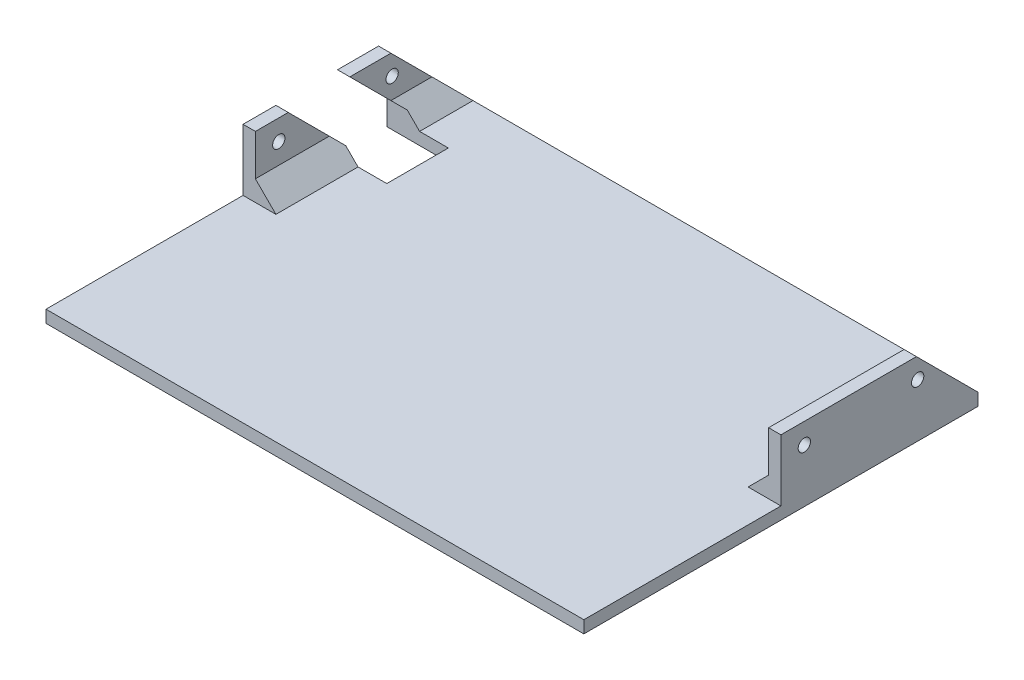
SolidWorks part; units mm, degrees
ref_plane "Front Plane" through (0, 0, 0) normal (0, 0, 1) x (1, 0, 0)
ref_plane "Top Plane" through (0, 0, 0) normal (0, 1, 0) x (1, 0, 0)
ref_plane "Right Plane" through (0, 0, 0) normal (1, 0, 0) x (0, 0, -1)
sketch "Sketch1" plane through (0, 0, 0) normal (0, 1, 0) x (1, 0, 0)
  line L0 (0, 48) -> (0, -48) construction
  line L1 (65.5, -48) -> (-65.5, -48)
  line L2 (65.5, -48) -> (65.5, 48)
  line L3 (65.5, 48) -> (-65.5, 48)
  line L4 (-65.5, -48) -> (-65.5, 48)
  line L5 (65.5, -48) -> (-65.5, 48) construction
  line L6 (65.5, 48) -> (-65.5, -48) construction
  line L7 (-65.5, 0) -> (65.5, 0) construction
  point P0 (0, 0)
  dimension "D1" = 131
  dimension "D2" = 96
extrude "Boss-Extrude1" add sketch "Sketch1" along normal mid plane 3
sketch "Sketch2" plane through (-65.5, 0, 0) normal (-1, 0, 0) x (0, 0, 1)
  line L0 (-48, -1.5) -> (-33.3, -1.5) construction
  line L1 (48, -1.5) -> (-48, -1.5) construction
  line L2 (-33.3, -1.5) -> (-33.3, 11.5) construction
  line L3 (-48, 1.5) -> (-33, 16.5)
  line L4 (-33, 16.5) -> (0, 16.5)
  line L5 (0, 16.5) -> (0, 1.5)
  line L6 (48, 1.5) -> (-48, 1.5) construction
  circle A0 centre (-33.3, 11.5) radius 1.5
  circle A1 centre (-5.7, 11.5) radius 1.5
  point P16 (0, 0)
  point P17 (0, 1.5)
  line M5 (48, 1.5) -> (-48, 1.5)
  dimension "D1" = 14.7
  dimension "D3" = 3
  dimension "D5" = 27.6
  dimension "D6" = 5
  dimension "D2" = 13
  dimension "D4" = 45
extrude "Boss-Extrude2" add sketch "Sketch2" against normal blind 3 contours L5 L4 L3 A1 A0 M5
mirror "Mirror1" about plane through (0, 0, 0) normal (1, 0, 0) of "Boss-Extrude2"
chamfer "Chamfer1" distance 5 angle 45 2 edges at (62.5, 1.5, -24) (-62.5, 1.5, -24)
sketch "Sketch3" plane through (-65.5, 0, 0) normal (-1, 0, 0) x (0, 0, 1)
  line L0 (-20, -1.5) -> (-20, 4.5)
  line L2 (48, -1.5) -> (-48, -1.5) construction
  line L3 (-33, 16.5) -> (0, 16.5) construction
  line L4 (-20, 16.5) -> (-23, 16.5)
  line L5 (-35, 4.5) -> (-35, -1.5)
  line L6 (-35, -1.5) -> (-20, -1.5)
  line L7 (-48, 1.5) -> (-48, -1.5) construction
  line L10 (-23, 16.5) -> (-35, 4.5)
  line L11 (-48, 1.5) -> (-33, 16.5) construction
  line L12 (-20, 4.5) -> (-8, 16.5)
  line L13 (-8, 16.5) -> (-20, 16.5)
  point P17 (0, 0)
  point P18 (0, 0)
  point P19 (0, 0)
  dimension "D1" = 15
  dimension "D2" = 13
  dimension "D3" = 3
extrude "Cut-Extrude1" cut sketch "Sketch3" against normal blind 15
